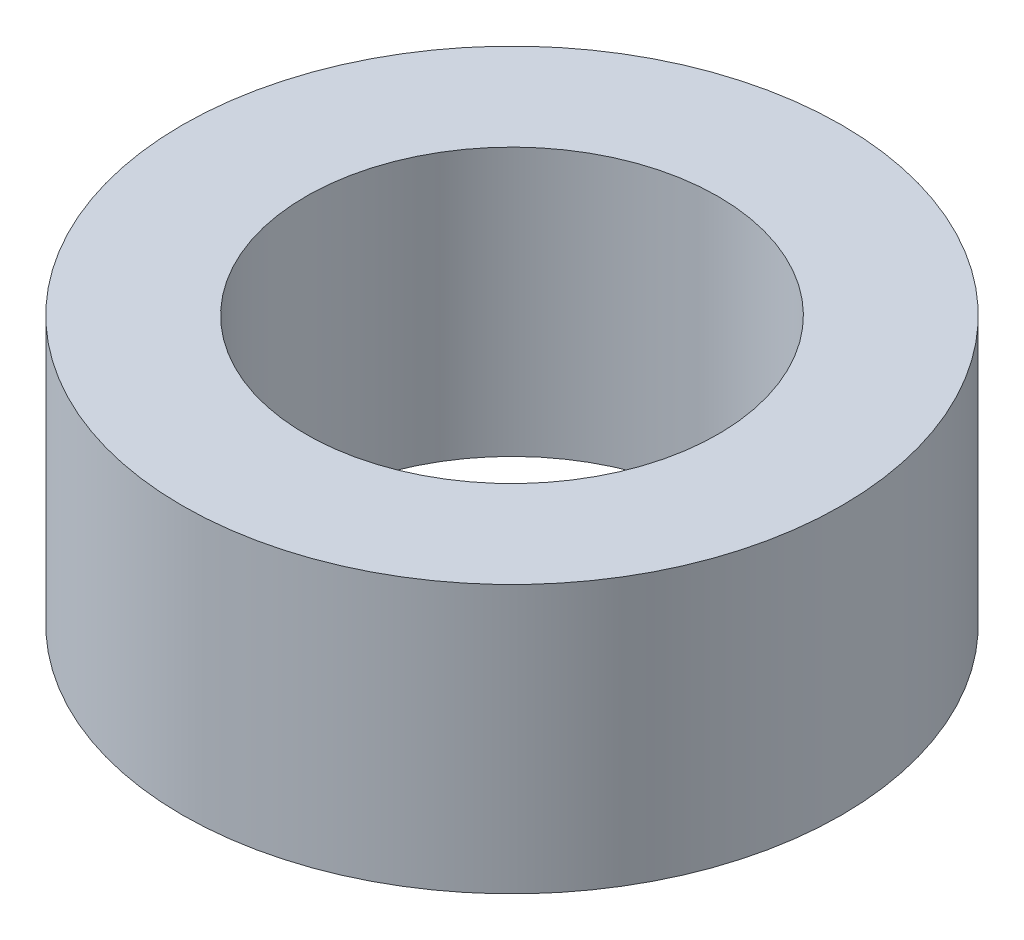
SolidWorks part; units mm, degrees
ref_plane "前视基准面" through (0, 0, 0) normal (0, 0, 1) x (1, 0, 0)
ref_plane "上视基准面" through (0, 0, 0) normal (0, 1, 0) x (1, 0, 0)
ref_plane "右视基准面" through (0, 0, 0) normal (1, 0, 0) x (0, 0, -1)
other "Configuration Table"
sketch "草图1" plane through (0, 0, 0) normal (0, 1, 0) x (1, 0, 0)
  circle A0 centre (0, 0) radius 2.5
  circle A1 centre (0, 0) radius 4
  dimension "D1" = 5
  dimension "D2" = 8
extrude "凸台-拉伸1" add sketch "草图1" along normal blind 3.25
